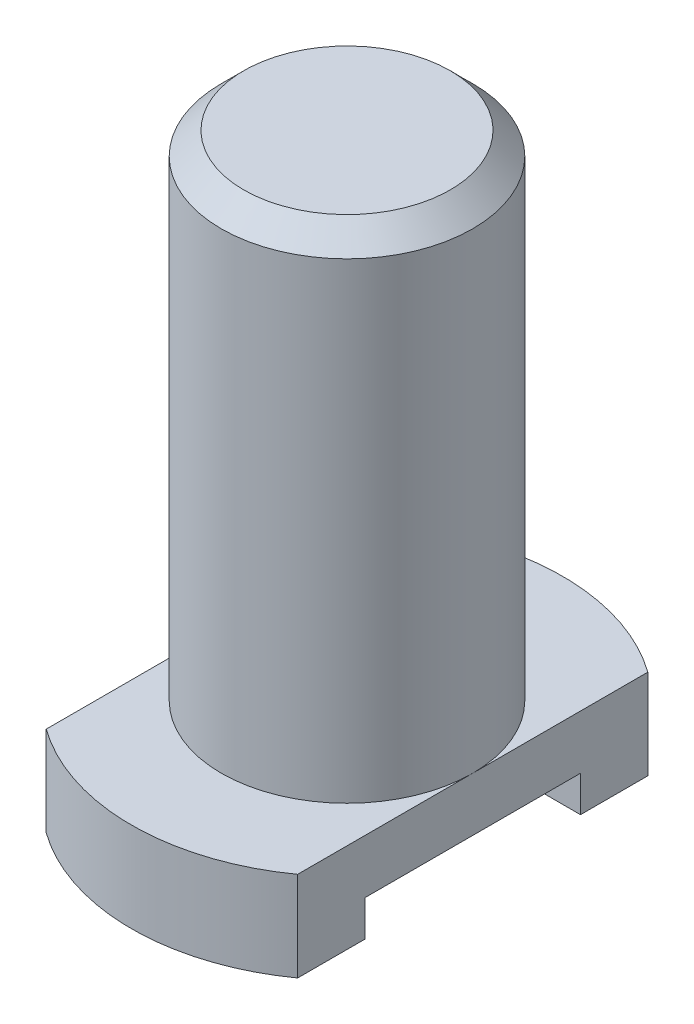
SolidWorks part; units mm, degrees
ref_plane "Front Plane" through (0, 0, 0) normal (0, 0, 1) x (1, 0, 0)
ref_plane "Top Plane" through (0, 0, 0) normal (0, 1, 0) x (1, 0, 0)
ref_plane "Right Plane" through (0, 0, 0) normal (1, 0, 0) x (0, 0, -1)
sketch "Sketch1" plane through (0, 0, 0) normal (0, 1, 0) x (1, 0, 0)
  circle A0 centre (0, 0) radius 1.4
  dimension "D1" = 2.8
extrude "Boss-Extrude3" add sketch "Sketch1" along normal blind 6.5
sketch "Sketch3" plane through (0, 0, 0) normal (0, 1, 0) x (1, 0, 0)
  line L0 (-1.4, -1.9494) -> (-1.4, 1.9494)
  line L1 (1.4, -1.9494) -> (1.4, 1.9494)
  circle A0 centre (0, 0) radius 2.4
  circle A1 centre (0, 0) radius 1.4
  circle A2 centre (0, 0) radius 1.4 construction
  dimension "D1" = 0
  dimension "D2" = 1
extrude "Boss-Extrude4" add sketch "Sketch3" along normal blind 1 contours L1 A0 L0
chamfer "Chamfer1" distance 0.25 angle 45 1 edges at (0, 6.5, 1.4)
sketch "Sketch4" plane through (1.4, 0, 0) normal (1, 0, 0) x (0, 0, -1)
  line L1 (-1.2, -0.4) -> (1.2, -0.4)
  line L2 (-1.2, -0.4) -> (-1.2, 0.4)
  line L3 (-1.2, 0.4) -> (1.2, 0.4)
  line L4 (1.2, -0.4) -> (1.2, 0.4)
  line L5 (-1.2, -0.4) -> (1.2, 0.4) construction
  line L6 (-1.2, 0.4) -> (1.2, -0.4) construction
  point P0 (0, 0)
  dimension "D1" = 2.4
  dimension "D2" = 0.8
extrude "Cut-Extrude1" cut sketch "Sketch4" against normal blind 3.6
